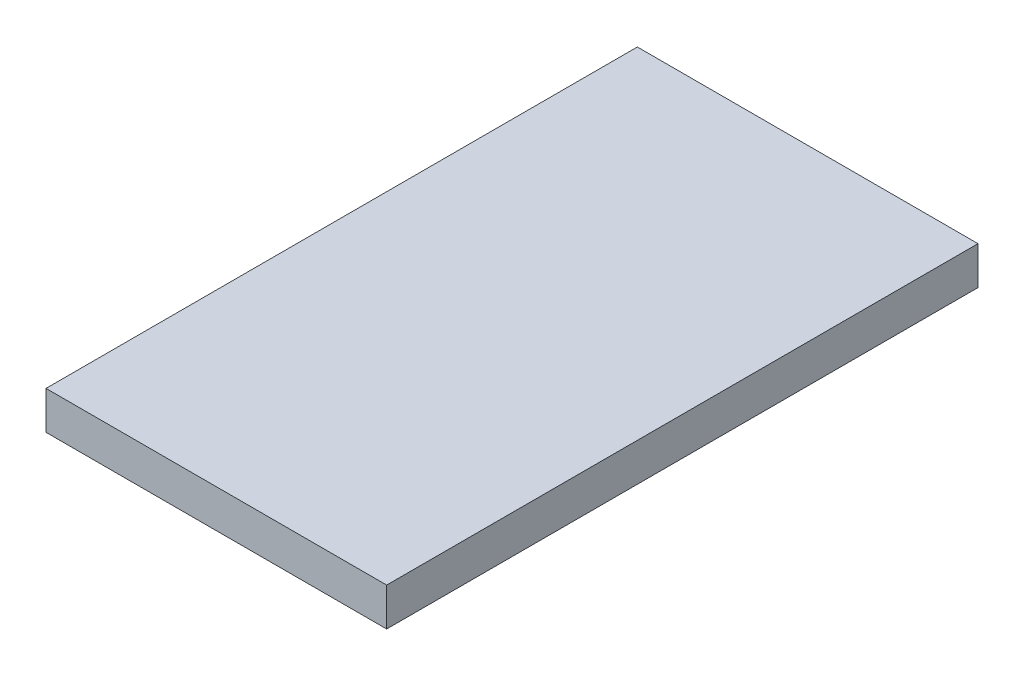
SolidWorks part; units mm, degrees
ref_plane "Front Plane" through (0, 0, 0) normal (0, 0, 1) x (1, 0, 0)
ref_plane "Top Plane" through (0, 0, 0) normal (0, 1, 0) x (1, 0, 0)
ref_plane "Right Plane" through (0, 0, 0) normal (1, 0, 0) x (0, 0, -1)
sketch "Sketch2" plane through (0, 0, 0) normal (0, 1, 0) x (1, 0, 0)
  line L1 (-8.9472, 15.5309) -> (8.9472, 15.5309)
  line L2 (-8.9472, 15.5309) -> (-8.9472, -15.5309)
  line L3 (-8.9472, -15.5309) -> (8.9472, -15.5309)
  line L4 (8.9472, 15.5309) -> (8.9472, -15.5309)
  line L5 (-8.9472, 15.5309) -> (8.9472, -15.5309) construction
  line L6 (-8.9472, -15.5309) -> (8.9472, 15.5309) construction
  point P0 (0, 0)
extrude "Boss-Extrude1" add sketch "Sketch2" along normal blind 2 contours L4 L3 L2 L1
sketch "Sketch3" plane through (0, 2, 0) normal (0, 1, 0) x (1, 0, 0)
  line L0 (4.5707, 15.5309) -> (4.5707, -15.4633) construction
  line L1 (-8.9472, 15.5309) -> (8.9472, 15.5309) construction
  point P2 (4.5707, 15.5309)
